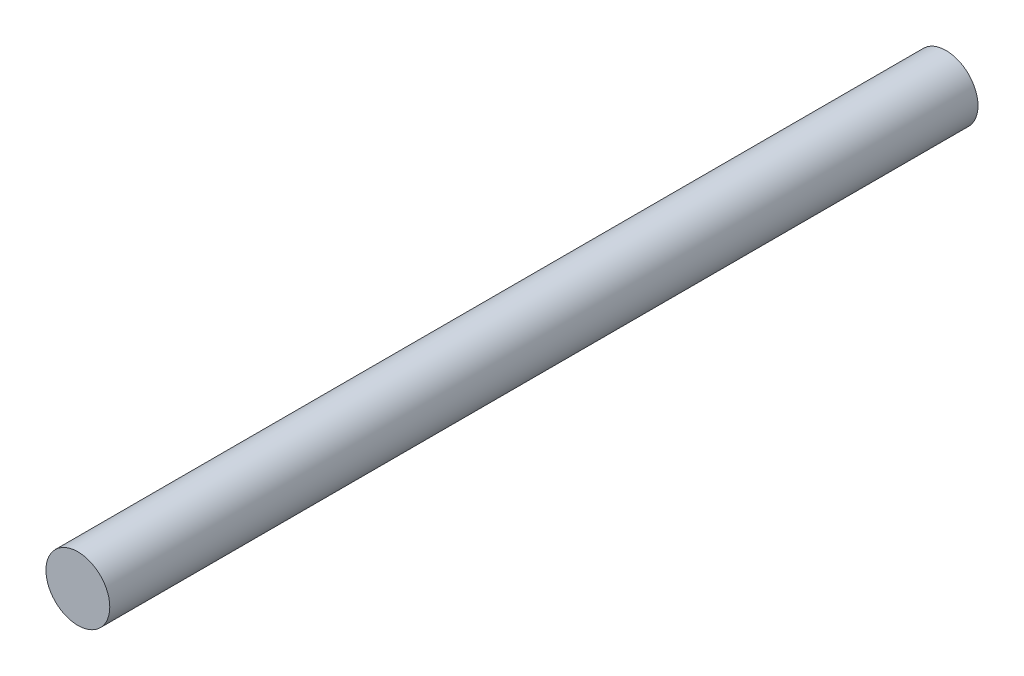
SolidWorks part; units mm, degrees
ref_plane "Front Plane" through (0, 0, 0) normal (0, 0, 1) x (1, 0, 0)
ref_plane "Top Plane" through (0, 0, 0) normal (0, 1, 0) x (1, 0, 0)
ref_plane "Right Plane" through (0, 0, 0) normal (1, 0, 0) x (0, 0, -1)
sketch "Sketch1" plane through (0, 0, 0) normal (0, 0, 1) x (1, 0, 0)
  circle A0 centre (0, 0) radius 2.5
  dimension "D1" = 5
extrude "Boss-Extrude1" add sketch "Sketch1" along normal blind 68
